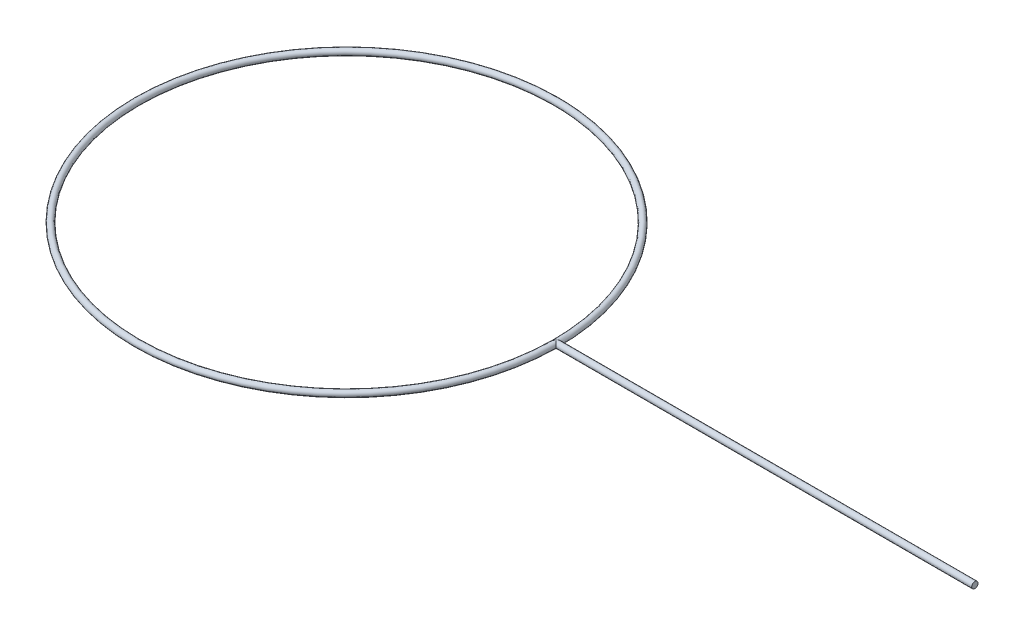
SolidWorks part; units mm, degrees
ref_plane "正面" through (0, 0, 0) normal (0, 0, 1) x (1, 0, 0)
ref_plane "平面" through (0, 0, 0) normal (0, 1, 0) x (1, 0, 0)
ref_plane "右側面" through (0, 0, 0) normal (1, 0, 0) x (0, 0, -1)
sketch "ｽｹｯﾁ1" plane through (0, 0, 0) normal (0, 0, 1) x (1, 0, 0)
  line L0 (-100, 40.1722) -> (-100, -46.9436) construction
  circle A1 centre (0, 0) radius 1.5
  dimension "D2" = 3
  dimension "D1" = 100
revolve "回転1" add sketch "ｽｹｯﾁ1" angle 360 about L0
sketch "ｽｹｯﾁ2" plane through (0, 0, 0) normal (1, 0, 0) x (0, 0, -1)
  circle A0 centre (0, 0) radius 1.5
extrude "ﾎﾞｽ - 押し出し1" add sketch "ｽｹｯﾁ2" along normal blind 200
